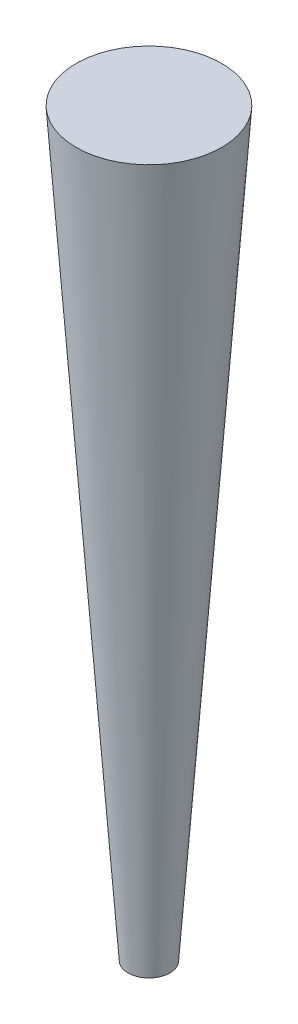
SolidWorks part; units mm, degrees
ref_plane "Front Plane" through (0, 0, 0) normal (0, 0, 1) x (1, 0, 0)
ref_plane "Top Plane" through (0, 0, 0) normal (0, 1, 0) x (1, 0, 0)
ref_plane "Right Plane" through (0, 0, 0) normal (1, 0, 0) x (0, 0, -1)
sketch "Sketch1" plane through (0, 0, 0) normal (0, 0, 1) x (1, 0, 0)
  line L0 (0, 0) -> (0, 300)
  line L1 (0, -55) -> (0, 55) construction
  line L2 (0, 300) -> (28.978, 300)
  line L3 (28.978, 300) -> (8, 0)
  line L4 (55, 0) -> (-55, 0) construction
  line L5 (8, 0) -> (0, 0)
  dimension "D1" = 8
  dimension "D2" = 4
  dimension "D3" = 300
revolve "Revolve1" add sketch "Sketch1" angle 360 about L0
sketch "Sketch2" plane through (0, 0, 0) normal (0, 0, 1) x (1, 0, 0)
  line L1 (-16.3664, 4.975) -> (12.859, 4.975)
  line L2 (-16.3664, 4.975) -> (-16.3664, -0.025)
  line L3 (-16.3664, -0.025) -> (12.859, -0.025)
  line L4 (12.859, 4.975) -> (12.859, -0.025)
  dimension "D1" = 5
extrude "Cut-Extrude1" cut sketch "Sketch2" against normal through all both and the other way through all
